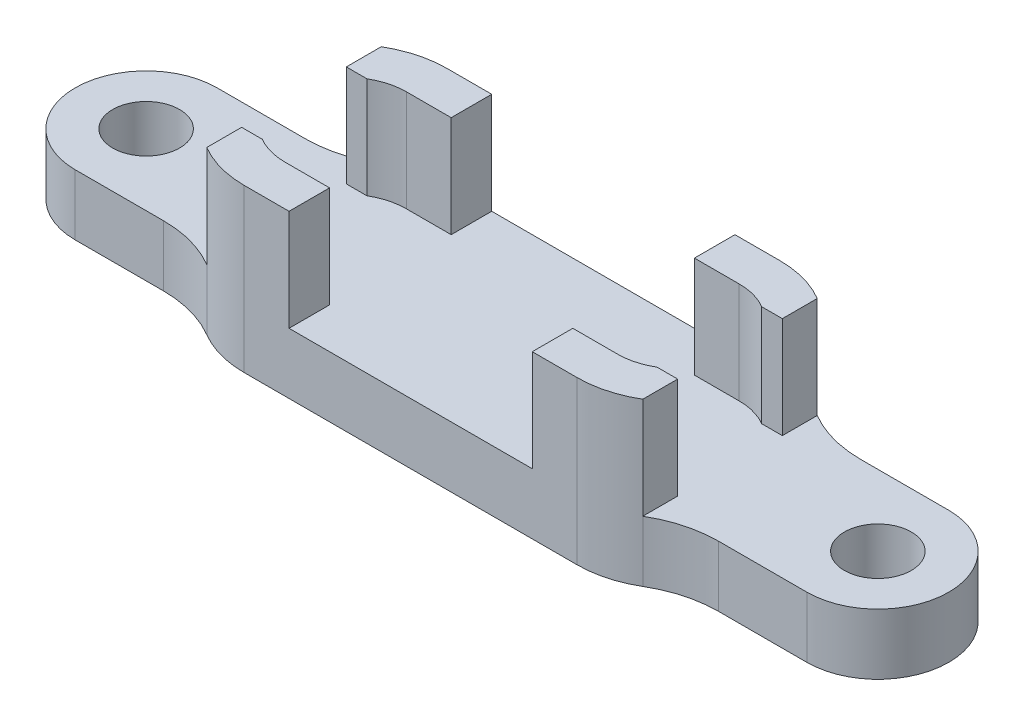
SolidWorks part; units mm, degrees
ref_plane "Front Plane" through (0, 0, 0) normal (0, 0, 1) x (1, 0, 0)
ref_plane "Top Plane" through (0, 0, 0) normal (0, 1, 0) x (1, 0, 0)
ref_plane "Right Plane" through (0, 0, 0) normal (1, 0, 0) x (0, 0, -1)
sketch "Sketch2" plane through (0, 0, 0) normal (0, 1, 0) x (1, 0, 0)
  line L0 (0, 3.5) -> (4.3567, 3.5)
  line L1 (0, -3.5) -> (4.3567, -3.5)
  line L2 (18.05, 13.7) -> (18.05, -9.7) construction
  line L3 (9.8393, -5) -> (26.2607, -5)
  line L4 (26.2607, 5) -> (9.8393, 5)
  line L5 (31.7433, 3.5) -> (36.1, 3.5)
  line L6 (31.7433, -3.5) -> (36.1, -3.5)
  arc A0 (0, 3.5) -> (0, -3.5) centre (0, 0) ccw
  arc A1 (36.1, -3.5) -> (36.1, 3.5) centre (36.1, 0) ccw
  arc A2 (7.2939, -4.3036) -> (9.8393, -5) centre (9.8393, 0) ccw
  arc A3 (9.8393, 5) -> (7.2939, 4.3036) centre (9.8393, 0) ccw
  arc A4 (26.2607, 5) -> (28.8061, 4.3036) centre (26.2607, 0) cw
  arc A5 (28.8061, -4.3036) -> (26.2607, -5) centre (26.2607, 0) cw
  arc A6 (28.8061, 4.3036) -> (31.7433, 3.5) centre (31.7433, 9.2695) ccw
  arc A7 (28.8061, -4.3036) -> (31.7433, -3.5) centre (31.7433, -9.2695) cw
  arc A8 (7.2939, -4.3036) -> (4.3567, -3.5) centre (4.3567, -9.2695) ccw
  arc A9 (7.2939, 4.3036) -> (4.3567, 3.5) centre (4.3567, 9.2695) cw
  circle A10 centre (0, 0) radius 1.65
  circle A11 centre (36.1, 0) radius 1.65
  dimension "D1" = 5.7695
  dimension "D2" = 3.5
  dimension "D3" = 3.3
  dimension "D4" = 3.3
extrude "Boss-Extrude1" add sketch "Sketch2" along normal blind 3
sketch "Sketch3" plane through (0, 3, 0) normal (0, 1, 0) x (1, 0, 0)
  line L0 (7.2939, 4.3036) -> (7.2939, 2.5822)
  line L1 (28.8061, 4.3036) -> (28.8061, 2.5822)
  line L2 (26.2607, 3) -> (24.05, 3)
  line L3 (9.8393, -3) -> (12.05, -3)
  line L4 (8.3121, 2.5822) -> (7.2939, 2.5822)
  line L5 (28.8061, 2.5822) -> (27.7879, 2.5822)
  line L6 (0, -3.5) -> (4.3567, -3.5)
  line L7 (9.8393, -5) -> (26.2607, -5)
  line L8 (31.7433, -3.5) -> (36.1, -3.5)
  line L9 (36.1, 3.5) -> (31.7433, 3.5)
  line L10 (26.2607, 5) -> (9.8393, 5)
  line L11 (4.3567, 3.5) -> (0, 3.5)
  line L13 (9.8393, -5) -> (12.05, -5)
  line L16 (26.2607, 5) -> (24.05, 5)
  line L18 (27.7879, -2.5822) -> (28.8061, -2.5822)
  line L19 (8.3121, -2.5822) -> (7.2939, -2.5822)
  line L20 (7.2939, -2.5822) -> (7.2939, -4.3036)
  line L21 (28.8061, -2.5822) -> (28.8061, -4.3036)
  line L22 (18.05, 5) -> (18.05, -5) construction
  line L23 (24.05, 5) -> (24.05, 3)
  line L24 (12.05, 5) -> (12.05, 3)
  line L25 (12.05, 5) -> (9.8393, 5)
  line L26 (26.2607, 5) -> (9.8393, 5) construction
  line L27 (12.05, 3) -> (9.8393, 3)
  line L28 (26.2607, 3) -> (9.8393, 3) construction
  line L29 (12.05, -3) -> (12.05, -5)
  line L30 (12.05, 5) -> (12.05, -5) construction
  line L31 (24.05, -3) -> (24.05, -5)
  line L32 (24.05, 5) -> (24.05, -5) construction
  line L33 (24.05, -3) -> (26.2607, -3)
  line L34 (9.8393, -3) -> (26.2607, -3) construction
  line L35 (24.05, -5) -> (26.2607, -5)
  line L36 (9.8393, -5) -> (26.2607, -5) construction
  arc A0 (27.7879, 2.5822) -> (26.2607, 3) centre (26.2607, 0) ccw
  arc A1 (9.8393, 3) -> (8.3121, 2.5822) centre (9.8393, 0) ccw
  arc A2 (8.3121, -2.5822) -> (9.8393, -3) centre (9.8393, 0) ccw
  arc A3 (26.2607, -3) -> (27.7879, -2.5822) centre (26.2607, 0) ccw
  arc A10 (0, 3.5) -> (0, -3.5) centre (0, 0) ccw
  arc A11 (7.2939, -4.3036) -> (4.3567, -3.5) centre (4.3567, -9.2695) ccw
  arc A12 (7.2939, -4.3036) -> (9.8393, -5) centre (9.8393, 0) ccw
  arc A13 (26.2607, -5) -> (28.8061, -4.3036) centre (26.2607, 0) ccw
  arc A14 (31.7433, -3.5) -> (28.8061, -4.3036) centre (31.7433, -9.2695) ccw
  arc A15 (36.1, -3.5) -> (36.1, 3.5) centre (36.1, 0) ccw
  arc A16 (28.8061, 4.3036) -> (31.7433, 3.5) centre (31.7433, 9.2695) ccw
  arc A17 (28.8061, 4.3036) -> (26.2607, 5) centre (26.2607, 0) ccw
  arc A18 (9.8393, 5) -> (7.2939, 4.3036) centre (9.8393, 0) ccw
  arc A19 (4.3567, 3.5) -> (7.2939, 4.3036) centre (4.3567, 9.2695) ccw
  arc A22 (7.2939, -4.3036) -> (9.8393, -5) centre (9.8393, 0) ccw
  arc A23 (26.2607, -5) -> (28.8061, -4.3036) centre (26.2607, 0) ccw
  arc A27 (28.8061, 4.3036) -> (26.2607, 5) centre (26.2607, 0) ccw
  arc A28 (9.8393, 5) -> (7.2939, 4.3036) centre (9.8393, 0) ccw
  dimension "D1" = 0
  dimension "D2" = 2
  dimension "D3" = 2
  dimension "D4" = 6
  dimension "D5" = 6
extrude "Boss-Extrude2" add sketch "Sketch3" along normal blind 5
